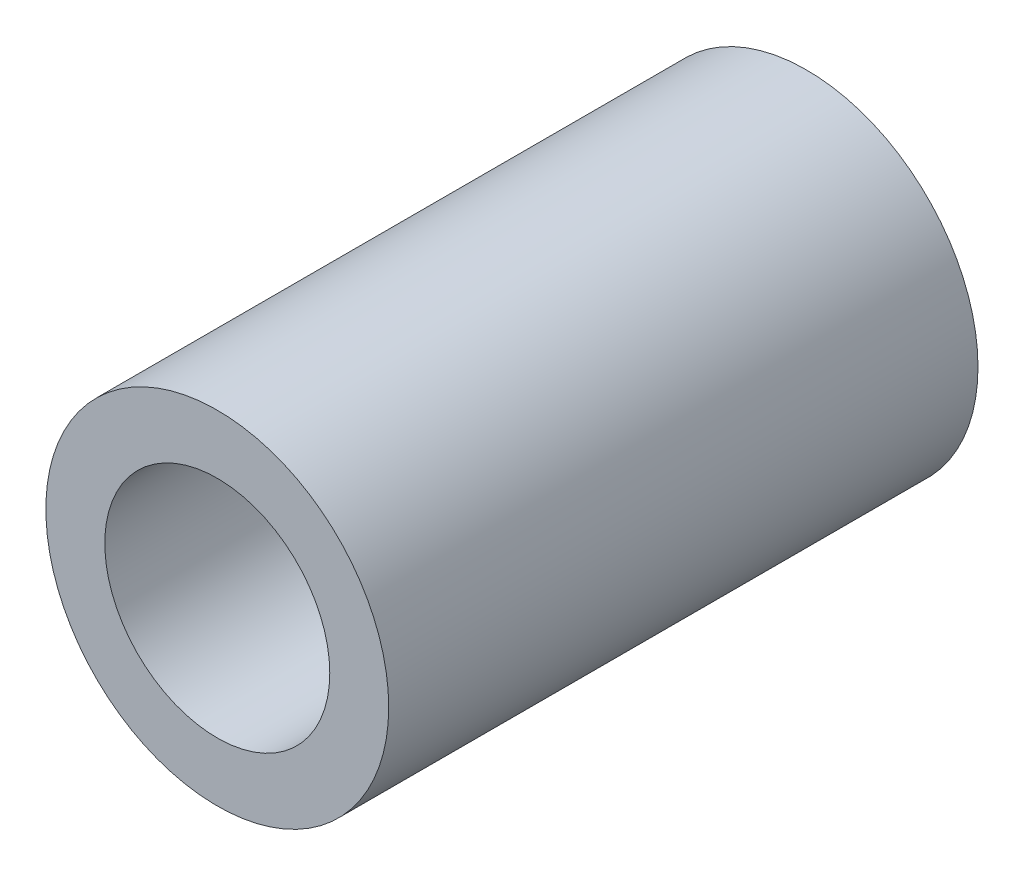
SolidWorks part; units mm, degrees
material "Plain Carbon Steel"
ref_plane "Front Plane" through (0, 0, 0) normal (0, 0, 1) x (1, 0, 0)
ref_plane "Top Plane" through (0, 0, 0) normal (0, 1, 0) x (1, 0, 0)
ref_plane "Right Plane" through (0, 0, 0) normal (1, 0, 0) x (0, 0, -1)
sketch "Sketch1" plane through (0, 0, 0) normal (0, 0, 1) x (1, 0, 0)
  circle A0 centre (0, 0) radius 5.25
  circle A1 centre (0, 0) radius 8
  dimension "D1" = 10.5
  dimension "D2" = 16
extrude "Boss-Extrude1" add sketch "Sketch1" along normal mid plane 27.5
